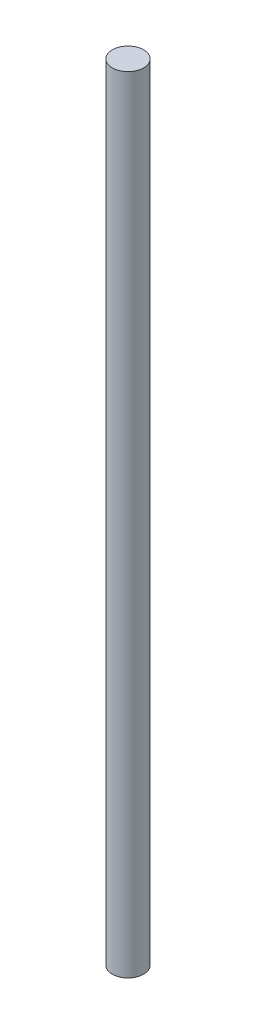
SolidWorks part; units mm, degrees
ref_plane "Front Plane" through (0, 0, 0) normal (0, 0, 1) x (1, 0, 0)
ref_plane "Top Plane" through (0, 0, 0) normal (0, 1, 0) x (1, 0, 0)
ref_plane "Right Plane" through (0, 0, 0) normal (1, 0, 0) x (0, 0, -1)
sketch "Sketch1" plane through (0, 0, 0) normal (0, 1, 0) x (1, 0, 0)
  circle A0 centre (0, 0) radius 20
  dimension "D1" = 40
extrude "Boss-Extrude2" add sketch "Sketch1" along normal blind 1000
